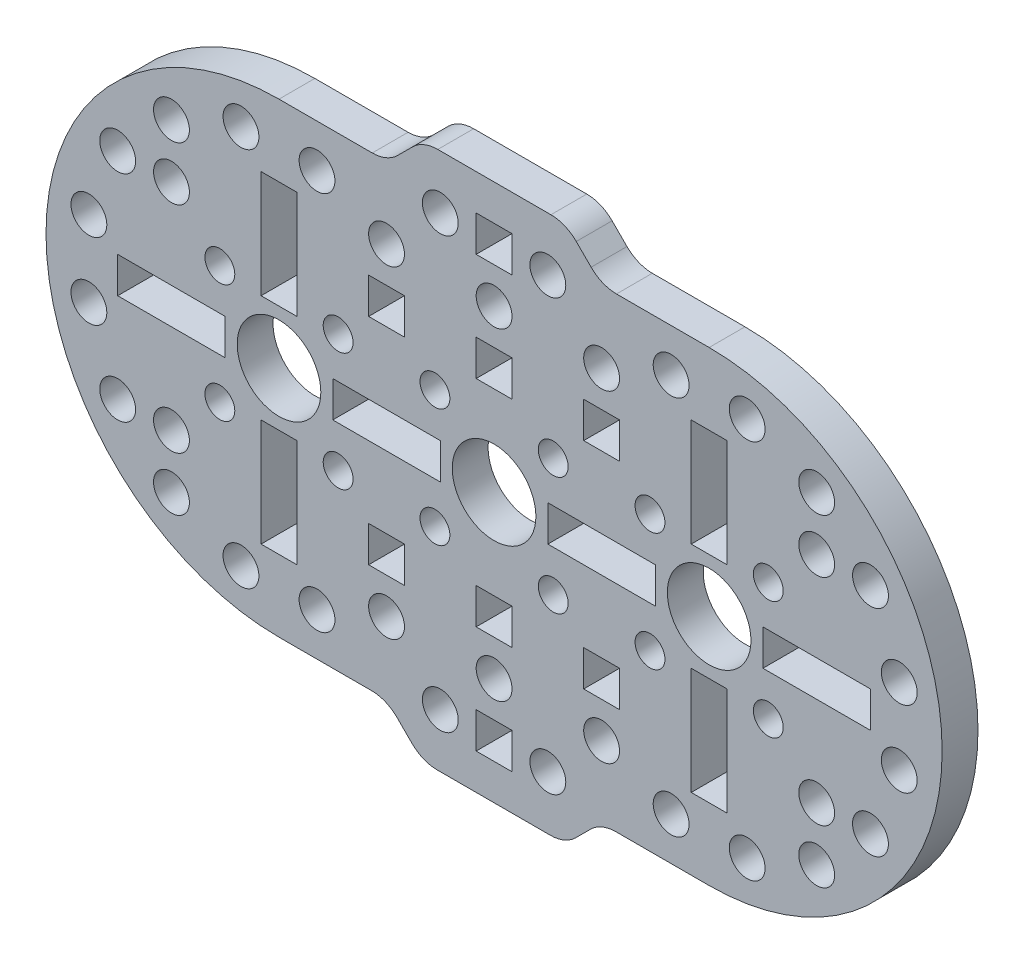
SolidWorks part; units mm, degrees
ref_plane "Alzado" through (0, 0, 0) normal (0, 0, 1) x (1, 0, 0)
ref_plane "Planta" through (0, 0, 0) normal (0, 1, 0) x (1, 0, 0)
ref_plane "Vista lateral" through (0, 0, 0) normal (1, 0, 0) x (0, 0, -1)
sketch "Model" plane through (0, 0, 0) normal (0, 0, 1) x (1, 0, 0)
  line L0 (32.2955, 274.8523) -> (41.2955, 274.8523)
  line L1 (32.2955, 277.8523) -> (32.2955, 274.8523)
  line L2 (41.2955, 277.8523) -> (32.2955, 277.8523)
  line L3 (41.2955, 274.8523) -> (41.2955, 277.8523)
  line L4 (29.2955, 280.8523) -> (29.2955, 289.8523)
  line L5 (26.2955, 280.8523) -> (29.2955, 280.8523)
  line L6 (26.2955, 289.8523) -> (26.2955, 280.8523)
  line L7 (29.2955, 289.8523) -> (26.2955, 289.8523)
  line L8 (23.2955, 277.8523) -> (14.2955, 277.8523)
  line L9 (23.2955, 274.8523) -> (23.2955, 277.8523)
  line L10 (14.2955, 274.8523) -> (23.2955, 274.8523)
  line L11 (14.2955, 277.8523) -> (14.2955, 274.8523)
  line L12 (26.2955, 271.8523) -> (26.2955, 262.8523)
  line L13 (29.2955, 271.8523) -> (26.2955, 271.8523)
  line L14 (29.2955, 262.8523) -> (29.2955, 271.8523)
  line L15 (26.2955, 262.8523) -> (29.2955, 262.8523)
  line L16 (68.2955, 274.8523) -> (77.2955, 274.8523)
  line L17 (68.2955, 277.8523) -> (68.2955, 274.8523)
  line L18 (77.2955, 277.8523) -> (68.2955, 277.8523)
  line L19 (77.2955, 274.8523) -> (77.2955, 277.8523)
  line L20 (65.2955, 280.8523) -> (65.2955, 289.8523)
  line L21 (62.2955, 280.8523) -> (65.2955, 280.8523)
  line L22 (62.2955, 289.8523) -> (62.2955, 280.8523)
  line L23 (65.2955, 289.8523) -> (62.2955, 289.8523)
  line L24 (59.2955, 277.8523) -> (50.2955, 277.8523)
  line L25 (59.2955, 274.8523) -> (59.2955, 277.8523)
  line L26 (50.2955, 274.8523) -> (59.2955, 274.8523)
  line L27 (50.2955, 277.8523) -> (50.2955, 274.8523)
  line L28 (62.2955, 271.8523) -> (62.2955, 262.8523)
  line L29 (65.2955, 271.8523) -> (62.2955, 271.8523)
  line L30 (65.2955, 262.8523) -> (65.2955, 271.8523)
  line L31 (62.2955, 262.8523) -> (65.2955, 262.8523)
  line L32 (35.2955, 286.8523) -> (35.2955, 283.8523)
  line L33 (38.2955, 286.8523) -> (35.2955, 286.8523)
  line L34 (38.2955, 283.8523) -> (38.2955, 286.8523)
  line L35 (35.2955, 283.8523) -> (38.2955, 283.8523)
  line L36 (44.2955, 286.8523) -> (44.2955, 283.8523)
  line L37 (47.2955, 286.8523) -> (44.2955, 286.8523)
  line L38 (47.2955, 283.8523) -> (47.2955, 286.8523)
  line L39 (44.2955, 283.8523) -> (47.2955, 283.8523)
  line L40 (53.2955, 286.8523) -> (53.2955, 283.8523)
  line L41 (56.2955, 286.8523) -> (53.2955, 286.8523)
  line L42 (56.2955, 283.8523) -> (56.2955, 286.8523)
  line L43 (53.2955, 283.8523) -> (56.2955, 283.8523)
  line L44 (35.2955, 268.8523) -> (35.2955, 265.8523)
  line L45 (38.2955, 268.8523) -> (35.2955, 268.8523)
  line L46 (38.2955, 265.8523) -> (38.2955, 268.8523)
  line L47 (35.2955, 265.8523) -> (38.2955, 265.8523)
  line L48 (44.2955, 268.8523) -> (44.2955, 265.8523)
  line L49 (47.2955, 268.8523) -> (44.2955, 268.8523)
  line L50 (47.2955, 265.8523) -> (47.2955, 268.8523)
  line L51 (44.2955, 265.8523) -> (47.2955, 265.8523)
  line L52 (53.2955, 268.8523) -> (53.2955, 265.8523)
  line L53 (56.2955, 268.8523) -> (53.2955, 268.8523)
  line L54 (56.2955, 265.8523) -> (56.2955, 268.8523)
  line L55 (53.2955, 265.8523) -> (56.2955, 265.8523)
  line L56 (44.2955, 295.8523) -> (44.2955, 292.8523)
  line L57 (47.2955, 295.8523) -> (44.2955, 295.8523)
  line L58 (47.2955, 292.8523) -> (47.2955, 295.8523)
  line L59 (44.2955, 292.8523) -> (47.2955, 292.8523)
  line L60 (44.2955, 259.8523) -> (44.2955, 256.8523)
  line L61 (47.2955, 259.8523) -> (44.2955, 259.8523)
  line L62 (47.2955, 256.8523) -> (47.2955, 259.8523)
  line L63 (44.2955, 256.8523) -> (47.2955, 256.8523)
  line L64 (63.7955, 295.8523) -> (56.0382, 295.8523)
  line L65 (63.7955, 256.8523) -> (55.9911, 256.8523)
  line L66 (27.7955, 295.8523) -> (35.5999, 295.8523)
  line L67 (27.7955, 256.8523) -> (35.5529, 256.8523)
  line L68 (53.9169, 296.731) -> (52.6742, 297.9736)
  line L70 (37.7213, 296.731) -> (38.9639, 297.9736)
  line L71 (41.0852, 298.8523) -> (50.5529, 298.8523)
  line L72 (53.8698, 255.9736) -> (52.6272, 254.731)
  line L74 (37.6742, 255.9736) -> (38.9169, 254.731)
  line L75 (41.0382, 253.8523) -> (50.5059, 253.8523)
  circle A0 centre (22.8458, 281.302) radius 1.25
  circle A1 centre (22.8458, 271.4025) radius 1.25
  circle A2 centre (32.7453, 271.4025) radius 1.25
  circle A3 centre (32.7453, 281.302) radius 1.25
  circle A4 centre (27.7955, 276.3523) radius 3.5
  circle A5 centre (18.7955, 289.8523) radius 1.5
  circle A6 centre (18.7955, 262.8523) radius 1.5
  circle A7 centre (36.7955, 289.8523) radius 1.5
  circle A8 centre (36.7955, 262.8523) radius 1.5
  circle A9 centre (14.2955, 267.3523) radius 1.5
  circle A10 centre (14.2955, 285.3523) radius 1.5
  circle A11 centre (30.9775, 292.2622) radius 1.5
  circle A12 centre (24.6136, 260.4424) radius 1.5
  circle A13 centre (30.9775, 260.4424) radius 1.5
  circle A14 centre (24.6136, 292.2622) radius 1.5
  circle A15 centre (11.8856, 279.5343) radius 1.5
  circle A16 centre (11.8856, 273.1703) radius 1.5
  circle A17 centre (58.8458, 281.302) radius 1.25
  circle A18 centre (58.8458, 271.4025) radius 1.25
  circle A19 centre (68.7453, 271.4025) radius 1.25
  circle A20 centre (68.7453, 281.302) radius 1.25
  circle A21 centre (54.7955, 289.8523) radius 1.5
  circle A22 centre (54.7955, 262.8523) radius 1.5
  circle A23 centre (72.7955, 289.8523) radius 1.5
  circle A24 centre (72.7955, 262.8523) radius 1.5
  circle A25 centre (77.2955, 267.3523) radius 1.5
  circle A26 centre (77.2955, 285.3523) radius 1.5
  circle A27 centre (66.9775, 292.2622) radius 1.5
  circle A28 centre (60.6136, 260.4424) radius 1.5
  circle A29 centre (66.9775, 260.4424) radius 1.5
  circle A30 centre (60.6136, 292.2622) radius 1.5
  circle A31 centre (79.7054, 273.1703) radius 1.5
  circle A32 centre (79.7054, 279.5343) radius 1.5
  circle A33 centre (63.7955, 276.3523) radius 3.5
  circle A34 centre (18.7955, 285.3523) radius 1.5
  circle A35 centre (18.7955, 267.3523) radius 1.5
  circle A36 centre (72.7955, 285.3523) radius 1.5
  circle A37 centre (72.7955, 267.3523) radius 1.5
  arc A38 (63.7955, 256.8523) -> (63.7955, 295.8523) centre (63.7955, 276.3523) ccw
  arc A39 (27.7955, 295.8523) -> (27.7955, 256.8523) centre (27.7955, 276.3523) ccw
  circle A40 centre (40.8458, 281.302) radius 1.25
  circle A41 centre (40.8458, 271.4025) radius 1.25
  circle A42 centre (50.7453, 271.4025) radius 1.25
  circle A43 centre (50.7453, 281.302) radius 1.25
  circle A44 centre (45.7955, 276.3523) radius 3.5
  circle A45 centre (41.2955, 294.3523) radius 1.5
  circle A46 centre (50.2955, 294.3523) radius 1.5
  circle A47 centre (45.7955, 289.8523) radius 1.5
  circle A48 centre (41.2955, 258.3523) radius 1.5
  circle A49 centre (50.2955, 258.3523) radius 1.5
  circle A50 centre (45.7955, 262.8523) radius 1.5
  arc A51 (53.9169, 296.731) -> (56.0382, 295.8523) centre (56.0382, 298.8523) ccw
  arc A52 (52.6742, 297.9736) -> (50.5529, 298.8523) centre (50.5529, 295.8523) ccw
  arc A53 (35.5999, 295.8523) -> (37.7213, 296.731) centre (35.5999, 298.8523) ccw
  arc A54 (41.0852, 298.8523) -> (38.9639, 297.9736) centre (41.0852, 295.8523) ccw
  arc A55 (55.9911, 256.8523) -> (53.8698, 255.9736) centre (55.9911, 253.8523) ccw
  arc A56 (50.5059, 253.8523) -> (52.6272, 254.731) centre (50.5059, 256.8523) ccw
  arc A57 (37.6742, 255.9736) -> (35.5529, 256.8523) centre (35.5529, 253.8523) ccw
  arc A58 (38.9169, 254.731) -> (41.0382, 253.8523) centre (41.0382, 256.8523) ccw
extrude "Saliente-Extruir1" add sketch "Model" along normal blind 3
